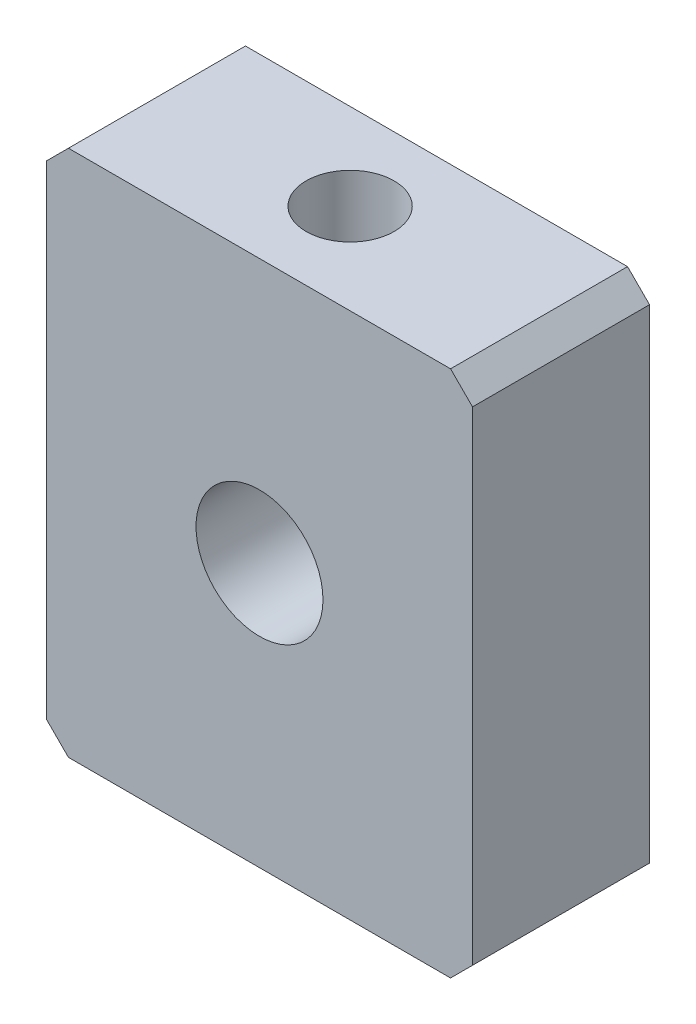
SolidWorks part; units mm, degrees
ref_plane "前视基准面" through (0, 0, 0) normal (0, 0, 1) x (1, 0, 0)
ref_plane "上视基准面" through (0, 0, 0) normal (0, 1, 0) x (1, 0, 0)
ref_plane "右视基准面" through (0, 0, 0) normal (1, 0, 0) x (0, 0, -1)
other "Configuration Table"
sketch "草图1" plane through (0, 0, -85) normal (0, 0, 1) x (1, 0, 0)
  line L0 (-311.3015, 562.4421) -> (-311.3015, 765.5381) construction
  line L1 (-408.2115, 562.4421) -> (-311.3015, 562.4421)
  line L2 (-408.2115, 562.4421) -> (-408.2115, 682.4421)
  line L3 (-408.2115, 682.4421) -> (-311.3015, 682.4421)
  line L4 (-311.3015, 562.4421) -> (-311.3015, 682.4421)
  line L5 (-359.7565, 682.4421) -> (-359.7565, 622.4421) construction
  circle A0 centre (-359.7565, 622.4421) radius 14.4381
  dimension "D2" = 60
  dimension "D1" = 120
extrude "凸台-拉伸2" add sketch "草图1" against normal up to surface (40.26 mm away)
chamfer "倒角1" distance 5 angle 45 4 edges at (-408.2115, 562.4421, -105.13) (-311.3015, 562.4421, -105.13) (-311.3015, 682.4421, -105.13) (-408.2115, 682.4421, -105.13)
sketch "草图2" plane through (0, 682.4421, 0) normal (0, 1, 0) x (1, 0, 0)
  circle A0 centre (-359.7565, 105.61) radius 10
extrude "切除-拉伸1" cut sketch "草图2" against normal blind 20
